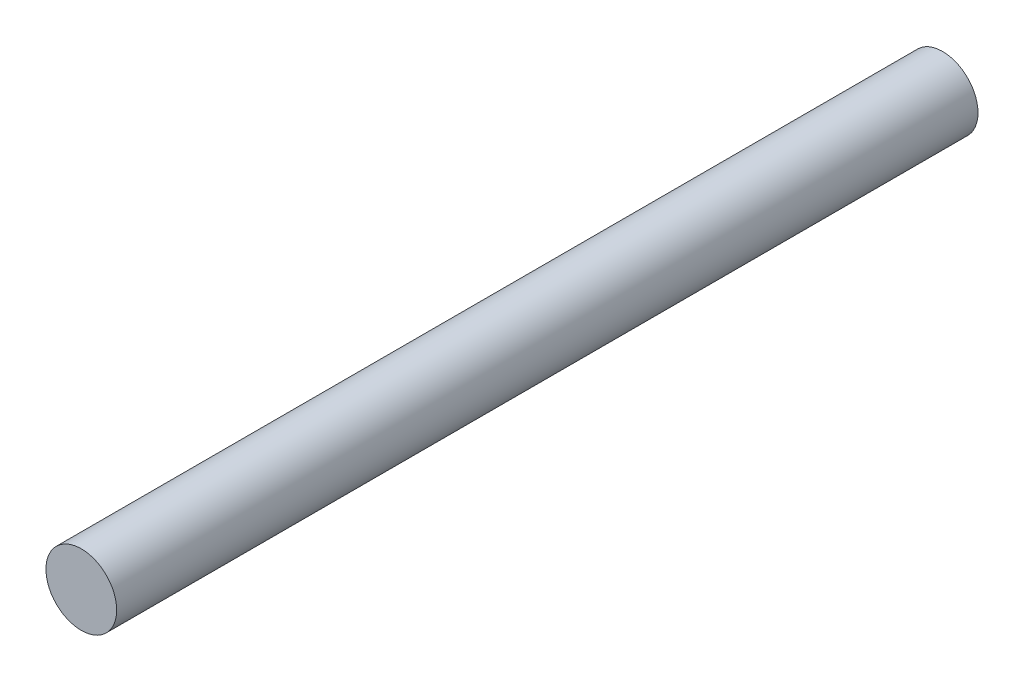
SolidWorks part; units mm, degrees
ref_plane "Front Plane" through (0, 0, 0) normal (0, 0, 1) x (1, 0, 0)
ref_plane "Top Plane" through (0, 0, 0) normal (0, 1, 0) x (1, 0, 0)
ref_plane "Right Plane" through (0, 0, 0) normal (1, 0, 0) x (0, 0, -1)
sketch "Sketch1" plane through (0, 0, 0) normal (0, 0, 1) x (1, 0, 0)
  circle A0 centre (0, 1.0197) radius 2
  dimension "D1" = 4
extrude "Boss-Extrude1" add sketch "Sketch1" along normal blind 48.7
